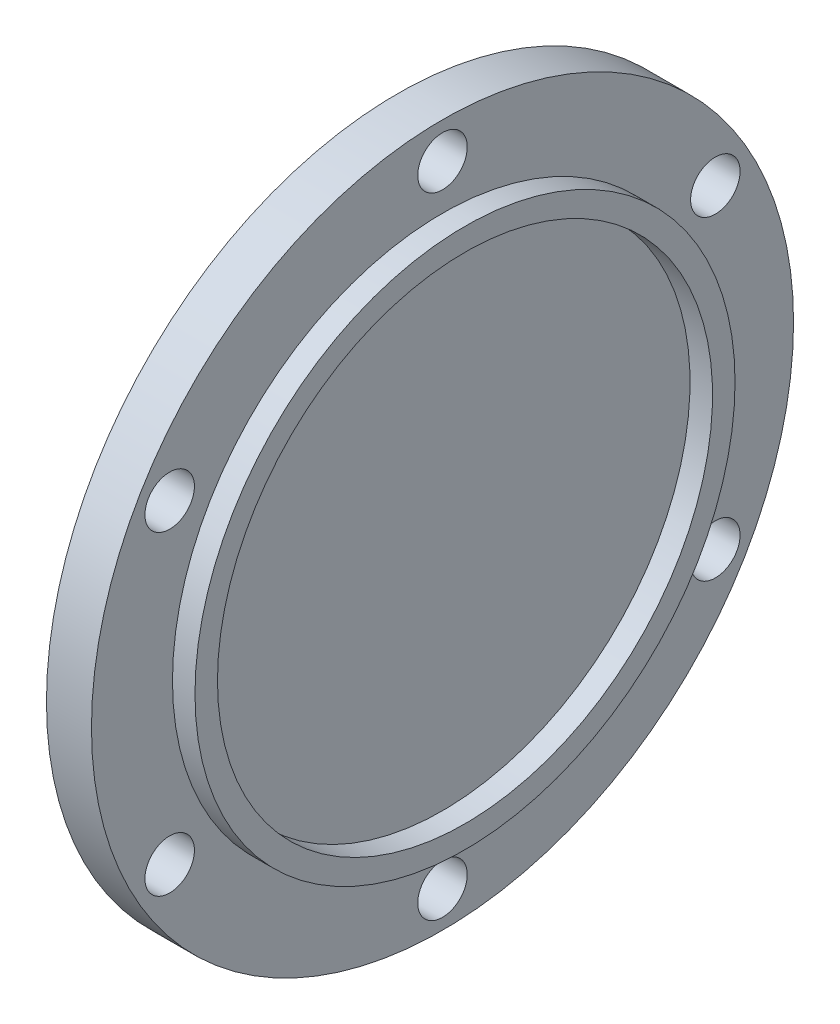
SolidWorks part; units mm, degrees
ref_plane "Front Plane" through (0, 0, 0) normal (0, 0, 1) x (1, 0, 0)
ref_plane "Top Plane" through (0, 0, 0) normal (0, 1, 0) x (1, 0, 0)
ref_plane "Right Plane" through (0, 0, 0) normal (1, 0, 0) x (0, 0, -1)
sketch "Sketch1" plane through (0, 0, 0) normal (0, 0, 1) x (1, 0, 0)
  line L0 (10, 78) -> (0, 78)
  line L1 (0, 78) -> (0, 0)
  line L2 (0, 0) -> (10, 0)
  line L3 (55, 0) -> (-55, 0) construction
  line L4 (10, 0) -> (10, 55)
  line L5 (10, 55) -> (15, 55)
  line L6 (15, 55) -> (15, 60)
  line L7 (15, 60) -> (10, 60)
  line L8 (10, 60) -> (10, 78)
  point P11 (53.3651, 39.7623)
  dimension "D1" = 10
  dimension "D2" = 10
  dimension "D3" = 18
  dimension "D4" = 55
  dimension "D5" = 60
  dimension "D6" = 5
revolve "Revolve1" add sketch "Sketch1" angle 360 about L2
sketch "Sketch2" plane through (10, 0, 0) normal (1, 0, 0) x (0, 0, -1)
  line L0 (0, 0) -> (60.6218, 35) construction
  circle A0 centre (0, 0) radius 70
  circle A1 centre (60.6218, 35) radius 5.5
  dimension "D1" = 140
  dimension "D2" = 11
extrude "Cut-Extrude1" cut sketch "Sketch2" against normal blind 20 contours A1
pattern_circular "CirPattern1" count 6 over 360 about axis through (0, 0, 0) along (1, 0, 0) of "Cut-Extrude1"
